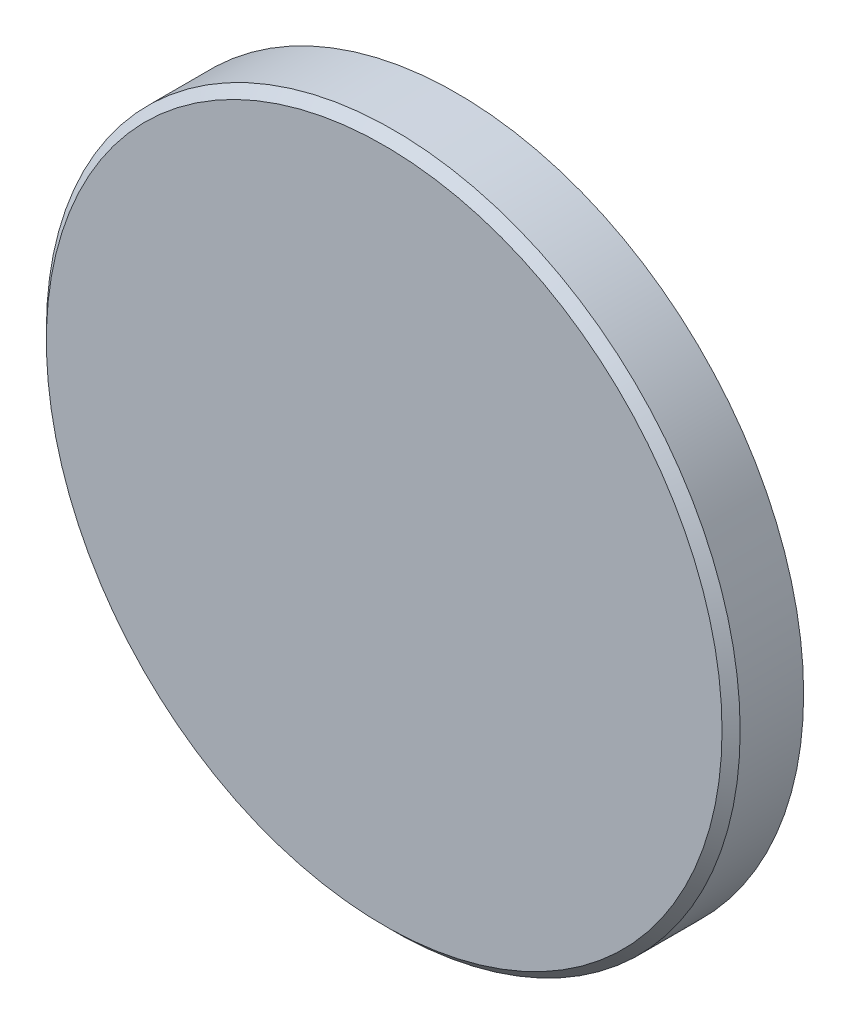
SolidWorks part; units mm, degrees
material "Acrylic (Medium-high impact)"
ref_plane "Front Plane" through (0, 0, 0) normal (0, 0, 1) x (1, 0, 0)
ref_plane "Top Plane" through (0, 0, 0) normal (0, 1, 0) x (1, 0, 0)
ref_plane "Right Plane" through (0, 0, 0) normal (1, 0, 0) x (0, 0, -1)
sketch "Sketch1" plane through (0, 0, 0) normal (0, 0, 1) x (1, 0, 0)
  circle A0 centre (0, 0) radius 9.5647
  dimension "D1" = 19.1293
extrude "Boss-Extrude1" add sketch "Sketch1" against normal blind 2
chamfer "Chamfer1" distance 0.25 angle 45 1 edges at (9.5647, 0, 0)
